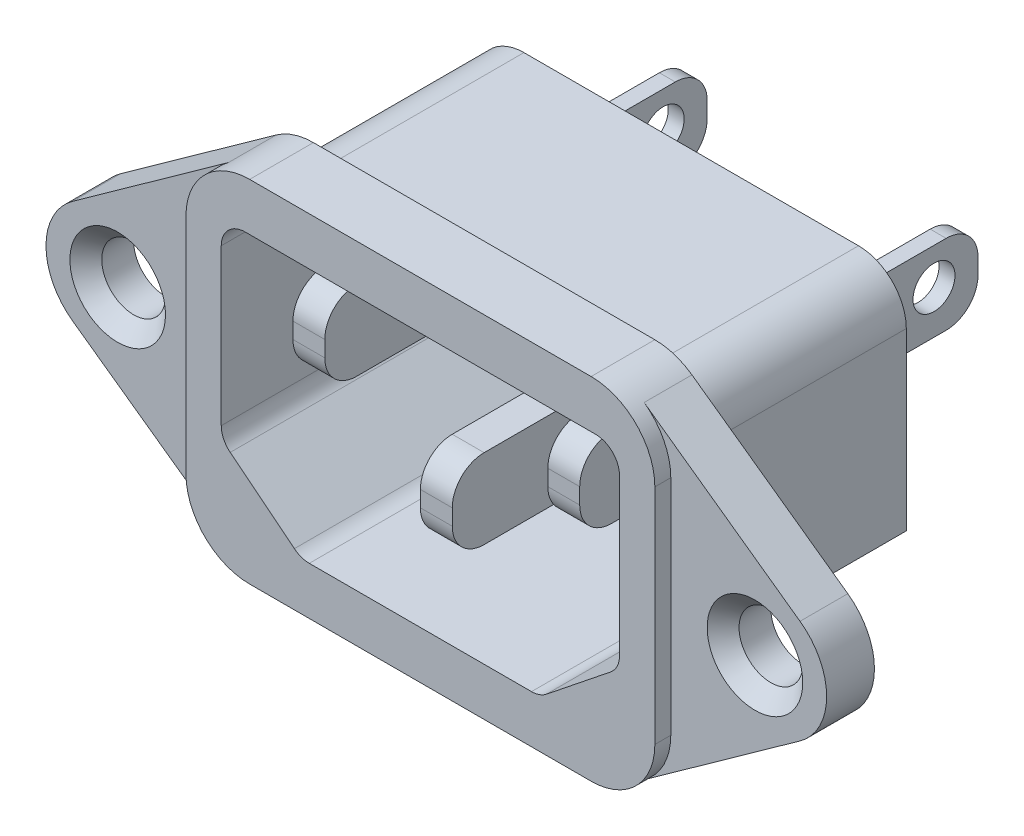
SolidWorks part; units mm, degrees
ref_plane "Спереди" through (0, 0, 0) normal (0, 0, 1) x (1, 0, 0)
ref_plane "Сверху" through (0, 0, 0) normal (0, 1, 0) x (1, 0, 0)
ref_plane "Справа" through (0, 0, 0) normal (1, 0, 0) x (0, 0, -1)
sketch "Эскиз1" plane through (0, 0, 0) normal (0, 0, 1) x (1, 0, 0)
  line L0 (-24.0375, 4.5702) -> (-3.0375, 4.5702)
  line L1 (-0.0375, 1.5702) -> (-0.0375, -9.4298)
  line L2 (-0.0375, -9.4298) -> (-5.5375, -14.4298)
  line L3 (-5.5375, -14.4298) -> (-21.5375, -14.4298)
  line L4 (-21.5375, -14.4298) -> (-27.0375, -9.4298)
  line L5 (-27.0375, -9.4298) -> (-27.0375, 1.5702)
  line L6 (-13.5375, 18.9838) -> (-13.5375, -41.5114) construction
  arc A0 (-3.0375, 4.5702) -> (-0.0375, 1.5702) centre (-3.0375, 1.5702) cw
  arc A1 (-24.0375, 4.5702) -> (-27.0375, 1.5702) centre (-24.0375, 1.5702) ccw
  point P10 (-0.0375, 4.5702)
  point P13 (-27.0375, 4.5702)
  dimension "D7" = 3
  dimension "D1" = 27
  dimension "D2" = 19
  dimension "D3" = 14
  dimension "D4" = 14
  dimension "D5" = 16
  dimension "D6" = 8
extrude "Бобышка-Вытянуть1" add sketch "Эскиз1" along normal blind 13
sketch "Эскиз2" plane through (0, 0, 13) normal (0, 0, 1) x (1, 0, 0)
  line L0 (-13.5375, 16.3919) -> (-13.5375, -22.6104) construction
  line L1 (-24.2536, 6.0702) -> (-2.8214, 6.0702)
  line L3 (-24.2542, -15.9298) -> (-2.8208, -15.9298)
  line L5 (-3.0375, 4.5702) -> (-24.0375, 4.5702) construction
  line L6 (-25.5375, 15.9017) -> (-25.5375, -21.6301) construction
  line L7 (-1.5375, 15.4116) -> (-1.5375, -25.5513) construction
  line L8 (-46.9216, -4.9319) -> (21.7701, -4.9319) construction
  line L9 (-26.5816, 5.323) -> (-36.3655, -1.6791)
  line L10 (-26.5813, -15.1832) -> (-36.3646, -8.1853)
  line L11 (-0.4935, 5.323) -> (9.2904, -1.6791)
  line L12 (-0.4937, -15.1832) -> (9.2896, -8.1853)
  arc A0 (9.2896, -8.1853) -> (9.2904, -1.6791) centre (6.9625, -4.9319) ccw
  arc A1 (-36.3655, -1.6791) -> (-36.3646, -8.1853) centre (-34.0375, -4.9319) ccw
  arc A2 (-26.5813, -15.1832) -> (-24.2542, -15.9298) centre (-24.2542, -11.9298) ccw
  arc A3 (-0.4937, -15.1832) -> (-2.8208, -15.9298) centre (-2.8208, -11.9298) cw
  arc A4 (-0.4935, 5.323) -> (-2.8214, 6.0702) centre (-2.8214, 2.0702) ccw
  arc A5 (-26.5816, 5.323) -> (-24.2536, 6.0702) centre (-24.2536, 2.0702) cw
  point P2 (-25.5375, -15.9298)
  point P21 (-1.5375, -15.9298)
  point P28 (-1.5375, 6.0702)
  point P31 (-25.5375, 6.0702)
  dimension "D3" = 4
  dimension "D1" = 22
  dimension "D2" = 1.5
  dimension "D5" = 12
  dimension "D6" = 12
extrude "Бобышка-Вытянуть2" add sketch "Эскиз2" along normal blind 3
sketch "Эскиз3" plane through (0, 0, 16) normal (0, 0, 1) x (1, 0, 0)
  line L0 (-24.2542, -15.9298) -> (-2.8208, -15.9298)
  line L1 (-24.2536, 6.0702) -> (-2.8214, 6.0702)
  line L2 (1.1786, 2.0702) -> (1.1792, -11.9297)
  line L3 (-28.2536, 2.0702) -> (-28.2542, -11.9298)
  arc A0 (-24.2536, 6.0702) -> (-28.2536, 2.0702) centre (-24.2536, 2.0702) ccw
  arc A1 (1.1786, 2.0702) -> (-2.8214, 6.0702) centre (-2.8214, 2.0702) ccw
  arc A2 (-28.2542, -11.9298) -> (-24.2542, -15.9298) centre (-24.2542, -11.9298) ccw
  arc A3 (-2.8208, -15.9298) -> (1.1792, -11.9297) centre (-2.8208, -11.9298) ccw
extrude "Бобышка-Вытянуть3" add sketch "Эскиз3" along normal blind 1
sketch "Эскиз4" plane through (0, 0, 17) normal (0, 0, 1) x (1, 0, 0)
  line L0 (-24.5375, 3.0702) -> (-2.5375, 3.0702)
  line L1 (-1.0375, 1.5702) -> (-1.0375, -8.2089)
  line L2 (-1.6005, -9.3802) -> (-5.6266, -12.6011)
  line L3 (-6.5637, -12.9298) -> (-20.5113, -12.9298)
  line L4 (-26.0375, 1.5702) -> (-26.0375, -8.2089)
  line L5 (-25.4746, -9.3802) -> (-21.4484, -12.6011)
  line L6 (-13.5375, 12.5615) -> (-13.5375, -18.3866) construction
  line L7 (-24.2542, -15.9298) -> (-2.8208, -15.9298) construction
  line L8 (-2.8214, 6.0702) -> (-24.2536, 6.0702) construction
  arc A0 (-26.0375, -8.2089) -> (-25.4746, -9.3802) centre (-24.5375, -8.2089) ccw
  arc A1 (-20.5113, -12.9298) -> (-21.4484, -12.6011) centre (-20.5113, -11.4298) cw
  arc A2 (-5.6266, -12.6011) -> (-6.5637, -12.9298) centre (-6.5637, -11.4298) cw
  arc A3 (-1.0375, -8.2089) -> (-1.6005, -9.3802) centre (-2.5375, -8.2089) cw
  arc A4 (-2.5375, 3.0702) -> (-1.0375, 1.5702) centre (-2.5375, 1.5702) cw
  arc A5 (-24.5375, 3.0702) -> (-26.0375, 1.5702) centre (-24.5375, 1.5702) ccw
  point P14 (-26.0375, -8.9298)
  point P17 (-21.0375, -12.9298)
  point P20 (-6.0375, -12.9298)
  point P23 (-1.0375, -8.9298)
  point P26 (-1.0375, 3.0702)
  point P29 (-26.0375, 3.0702)
  dimension "D9" = 1.5
  dimension "D1" = 12.5
  dimension "D2" = 12.5
  dimension "D3" = 3
  dimension "D4" = 3
  dimension "D5" = 7.5
  dimension "D6" = 7.5
  dimension "D7" = 12
  dimension "D8" = 12
extrude "Вырез-Вытянуть1" cut sketch "Эскиз4" against normal blind 16
sketch "Эскиз5" plane through (0, 0, 1) normal (0, 0, 1) x (1, 0, 0)
  line L0 (-13.5375, 12.8829) -> (-13.5375, -22.1444) construction
  line L1 (-22.5375, 0.7247) -> (-20.5375, 0.7247)
  line L2 (-22.5375, 0.7247) -> (-22.5375, -4.2753)
  line L3 (-22.5375, -4.2753) -> (-20.5375, -4.2753)
  line L4 (-20.5375, 0.7247) -> (-20.5375, -4.2753)
  line L5 (-14.5375, -4.4261) -> (-12.5375, -4.4261)
  line L6 (-14.5375, -4.4261) -> (-14.5375, -9.4261)
  line L7 (-14.5375, -9.4261) -> (-12.5375, -9.4261)
  line L8 (-12.5375, -4.4261) -> (-12.5375, -9.4261)
  line L9 (-6.5375, 0.7247) -> (-4.5375, 0.7247)
  line L10 (-6.5375, 0.7247) -> (-6.5375, -4.2753)
  line L11 (-6.5375, -4.2753) -> (-4.5375, -4.2753)
  line L12 (-4.5375, 0.7247) -> (-4.5375, -4.2753)
  dimension "D1" = 2
  dimension "D2" = 2
  dimension "D3" = 2
  dimension "D4" = 1
  dimension "D5" = 7
  dimension "D6" = 7
  dimension "D7" = 5
  dimension "D8" = 5
  dimension "D9" = 5
extrude "Бобышка-Вытянуть4" add sketch "Эскиз5" along normal blind 15
fillet "Скругление1" radius 2 6 edges at (-13.5375, -9.4261, 16) (-13.5375, -4.4261, 16) (-5.5375, -4.2753, 16) (-5.5375, 0.7247, 16) (-21.5375, -4.2753, 16) (-21.5375, 0.7247, 16)
sketch "Эскиз6" plane through (0, 0, 0) normal (0, 0, -1) x (-1, 0, 0)
  line L0 (12.5375, -4.4261) -> (14.5375, -4.4261) construction
  line L1 (4.5375, 0.7247) -> (5.5375, 0.7247)
  line L2 (4.5375, 0.7247) -> (4.5375, -4.2753)
  line L3 (4.5375, -4.2753) -> (5.5375, -4.2753)
  line L4 (5.5375, 0.7247) -> (5.5375, -4.2753)
  line L5 (22.5375, 0.7247) -> (21.5375, 0.7247)
  line L6 (22.5375, 0.7247) -> (22.5375, -4.2753)
  line L7 (22.5375, -4.2753) -> (21.5375, -4.2753)
  line L8 (21.5375, 0.7247) -> (21.5375, -4.2753)
  line L9 (13.129, -4.4261) -> (14.129, -4.4261)
  line L10 (13.129, -4.4261) -> (13.129, -9.4261)
  line L11 (13.129, -9.4261) -> (14.129, -9.4261)
  line L12 (14.129, -4.4261) -> (14.129, -9.4261)
  line L13 (13.5375, 11.8465) -> (13.5375, -19.6123) construction
  dimension "D1" = 8
  dimension "D2" = 8
  dimension "D3" = 1
  dimension "D4" = 5
  dimension "D5" = 5
  dimension "D6" = 5
extrude "Бобышка-Вытянуть5" add sketch "Эскиз6" along normal blind 9
sketch "Эскиз7" plane through (0, 0, 0) normal (0, 0, -1) x (-1, 0, 0)
  line L1 (3.63, 1.3262) -> (6.4899, 1.3262)
  line L2 (3.63, 1.3262) -> (3.63, -5.0064)
  line L3 (3.63, -5.0064) -> (6.4899, -5.0064)
  line L4 (6.4899, 1.3262) -> (6.4899, -5.0064)
  line L5 (12.4651, -3.7938) -> (14.8487, -3.7938)
  line L6 (12.4651, -3.7938) -> (12.4651, -10.0623)
  line L7 (12.4651, -10.0623) -> (14.8487, -10.0623)
  line L8 (14.8487, -3.7938) -> (14.8487, -10.0623)
  line L9 (20.7765, 1.3456) -> (23.317, 1.3456)
  line L10 (20.7765, 1.3456) -> (20.7765, -5.0064)
  line L11 (20.7765, -5.0064) -> (23.317, -5.0064)
  line L12 (23.317, 1.3456) -> (23.317, -5.0064)
extrude "Бобышка-Вытянуть7" add sketch "Эскиз7" along normal blind 1.5
sketch "Эскиз8" plane through (-4.5375, 0, 0) normal (1, 0, 0) x (0, 0, -1)
  circle A0 centre (6.2372, -1.5619) radius 1.3177
sketch "Эскиз9" plane through (-13.129, 0, 0) normal (1, 0, 0) x (0, 0, -1)
  circle A0 centre (6.2669, -6.9327) radius 1.3234
extrude "Вырез-Вытянуть2" cut sketch "Эскиз8" against normal blind 21.5
extrude "Вырез-Вытянуть3" cut sketch "Эскиз9" against normal blind 3.5
fillet "Скругление2" radius 2 6 edges at (-13.629, -9.4261, -9) (-13.629, -4.4261, -9) (-22.0375, -4.2753, -9) (-22.0375, 0.7247, -9) (-5.0375, -4.2753, -9) (-5.0375, 0.7247, -9)
sketch "Эскиз10" plane through (0, 0, 16) normal (0, 0, 1) x (1, 0, 0)
  line L0 (-13.5375, 6.0702) -> (-13.5375, -15.9298) construction
  line L1 (-2.8214, 6.0702) -> (-24.2536, 6.0702) construction
  line L2 (-24.2542, -15.9298) -> (-2.8208, -15.9298) construction
  line L3 (-38.0375, -4.9324) -> (10.9625, -4.9324) construction
  circle A0 centre (6.4625, -4.9319) radius 2
  arc A1 (-36.3655, -1.6791) -> (-36.3646, -8.1853) centre (-34.0375, -4.9319) ccw construction
  arc A2 (9.2896, -8.1853) -> (9.2904, -1.6791) centre (6.9625, -4.9319) ccw construction
  dimension "D1" = 20
extrude "Вырез-Вытянуть4" cut sketch "Эскиз10" against normal blind 3.5
sketch "Эскиз11" plane through (0, 0, 16) normal (0, 0, 1) x (1, 0, 0)
  line L0 (-13.5375, 6.0702) -> (-13.5375, -15.9298) construction
  line L1 (-2.8214, 6.0702) -> (-24.2536, 6.0702) construction
  line L2 (-24.2542, -15.9298) -> (-2.8208, -15.9298) construction
  line L3 (-13.5375, -15.9298) -> (-38.0375, -4.9324) construction
  line L4 (-38.0375, -4.9324) -> (10.9625, -4.9324) construction
  circle A0 centre (-33.5375, -4.9319) radius 2
  arc A1 (-36.3655, -1.6791) -> (-36.3646, -8.1853) centre (-34.0375, -4.9319) ccw construction
  arc A2 (9.2896, -8.1853) -> (9.2904, -1.6791) centre (6.9625, -4.9319) ccw construction
  dimension "D1" = 20
extrude "Вырез-Вытянуть5" cut sketch "Эскиз11" against normal blind 3.5
chamfer "Фаска1" distance 1 angle 45 2 edges at (8.4625, -4.9319, 16) (-31.5375, -4.9319, 16)
